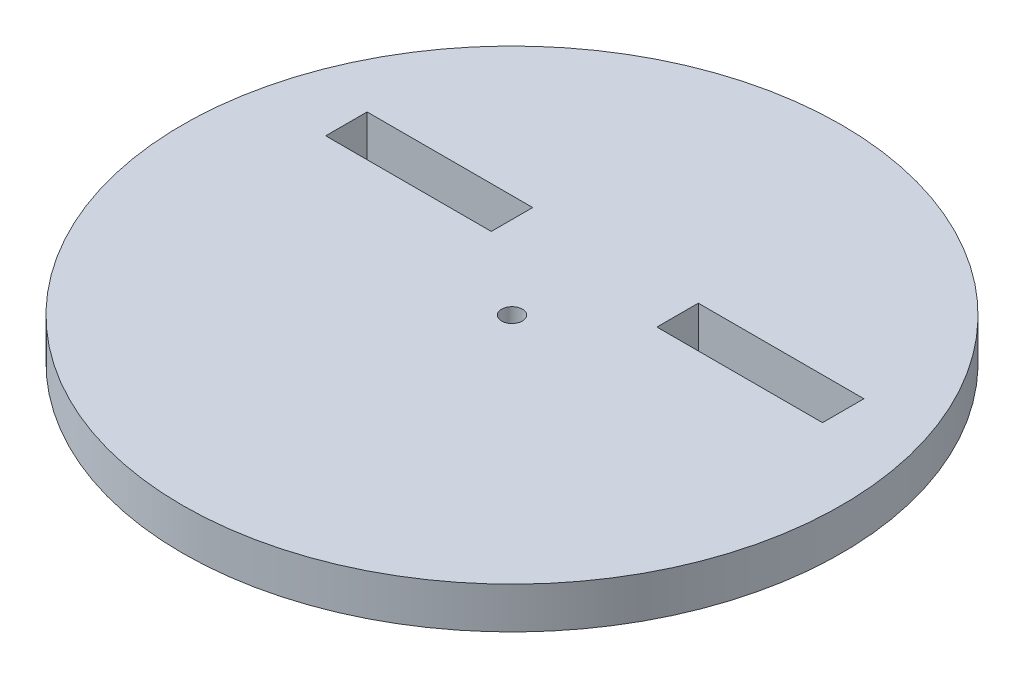
SolidWorks part; units mm, degrees
material "Maple"
ref_plane "Front Plane" through (0, 0, 0) normal (0, 0, 1) x (1, 0, 0)
ref_plane "Top Plane" through (0, 0, 0) normal (0, 1, 0) x (1, 0, 0)
ref_plane "Right Plane" through (0, 0, 0) normal (1, 0, 0) x (0, 0, -1)
sketch "Sketch1" plane through (0, 0, 0) normal (0, 1, 0) x (1, 0, 0)
  line L0 (-48.9245, 12.7) -> (48.9245, 12.7) construction
  line L1 (0, -50.546) -> (0, 50.546) construction
  line L2 (-38.1, 15.875) -> (-12.7, 15.875)
  line L3 (-38.1, 15.875) -> (-38.1, 9.525)
  line L4 (-38.1, 9.525) -> (-12.7, 9.525)
  line L5 (-12.7, 15.875) -> (-12.7, 9.525)
  line L6 (-38.1, 15.875) -> (-12.7, 9.525) construction
  line L7 (-38.1, 9.525) -> (-12.7, 15.875) construction
  line L8 (12.7, 15.875) -> (12.7, 9.525)
  line L9 (38.1, 9.525) -> (12.7, 9.525)
  line L10 (38.1, 15.875) -> (38.1, 9.525)
  line L11 (38.1, 15.875) -> (12.7, 15.875)
  circle A0 centre (0, 0) radius 1.5875
  circle A1 centre (0, 0) radius 50.546
  circle A2 centre (0, 0) radius 3.175 construction
  point P7 (-25.4, 12.7)
  point P14 (0, 0)
  point P15 (0, 0)
  dimension "D1" = 101.092
  dimension "D2" = 6.35
  dimension "D3" = 3.175
  dimension "D4" = 6.35
  dimension "D5" = 25.4
  dimension "D6" = 25.4
  dimension "D7" = 12.7
extrude "Boss-Extrude1" add sketch "Sketch1" along normal blind 6.35
